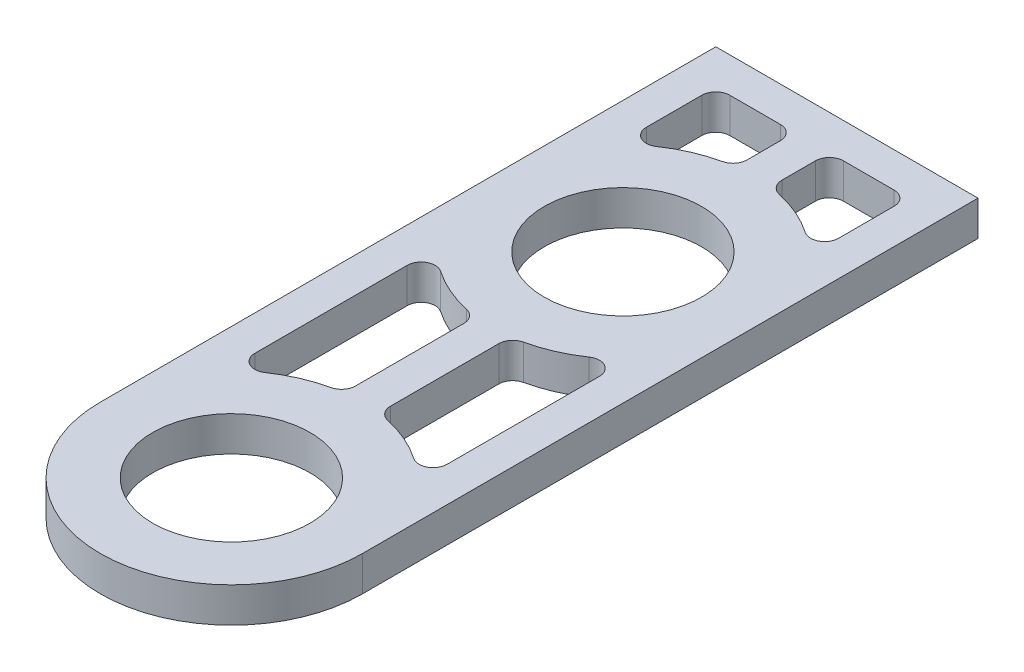
SolidWorks part; units mm, degrees
ref_plane "Front Plane" through (0, 0, 0) normal (0, 0, 1) x (1, 0, 0)
ref_plane "Top Plane" through (0, 0, 0) normal (0, 1, 0) x (1, 0, 0)
ref_plane "Right Plane" through (0, 0, 0) normal (1, 0, 0) x (0, 0, -1)
sketch "Sketch1" plane through (0, 0, 0) normal (0, 1, 0) x (1, 0, 0)
  line L0 (-23.8125, 67.2592) -> (23.8125, 67.2592) construction
  line L1 (-23.8125, -76.2) -> (23.8125, -76.2)
  line L2 (-23.8125, -76.2) -> (-23.8125, 76.2)
  line L3 (-23.8125, 76.2) -> (23.8125, 76.2)
  line L4 (23.8125, -76.2) -> (23.8125, 76.2)
  line L5 (-23.8125, -76.2) -> (23.8125, 76.2) construction
  line L6 (-23.8125, 76.2) -> (23.8125, -76.2) construction
  line L8 (7.3323, -35.6108) -> (3.6662, -29.2608)
  line L9 (3.6662, -29.2608) -> (-3.6662, -29.2608)
  line L10 (-3.6662, -29.2608) -> (-7.3323, -35.6108)
  line L11 (-7.3323, -35.6108) -> (-3.6662, -41.9608)
  line L12 (-3.6662, -41.9608) -> (3.6662, -41.9608)
  line L13 (3.6662, -41.9608) -> (7.3323, -35.6108)
  line L14 (5.4993, 35.5092) -> (2.7496, 40.2717)
  line L15 (2.7496, 40.2717) -> (-2.7496, 40.2717)
  line L16 (-2.7496, 40.2717) -> (-5.4993, 35.5092)
  line L17 (-5.4993, 35.5092) -> (-2.7496, 30.7467)
  line L18 (-2.7496, 30.7467) -> (2.7496, 30.7467)
  line L19 (2.7496, 30.7467) -> (5.4993, 35.5092)
  circle A0 centre (0, 35.5092) radius 14.2875
  circle A1 centre (0, 35.5092) radius 4.7625 construction
  circle A2 centre (0, -35.6108) radius 14.2875
  circle A3 centre (0, -35.6108) radius 6.35 construction
  circle A4 centre (0, 35.5092) radius 31.75
  circle A5 centre (0, -35.6108) radius 53.34
  point P0 (0, 0)
  dimension "D3" = 28.575
  dimension "D4" = 9.525
  dimension "D5" = 28.575
  dimension "D7" = 12.7
  dimension "D9" = 63.5
  dimension "D10" = 106.68
  dimension "D1" = 47.625
  dimension "D2" = 8.9408
  dimension "D6" = 71.12
  dimension "D8" = 152.4
  dimension "D11" = 31.75
extrude "Boss-Extrude1" add sketch "Sketch1" along normal blind 6.35 contours A4 A0 | L4 A5 L2 L1 A2 | A5 L4 L3 L2 A4 | A5 L4 A4 | A5 A4 L2 | A4 A5
sketch "Sketch2" plane through (0, 6.35, 0) normal (0, 1, 0) x (1, 0, 0)
  line L0 (-23.8125, 76.2) -> (23.8125, 76.2)
  line L1 (23.8125, 76.2) -> (23.8125, 38.1)
  line L2 (23.8125, -76.2) -> (23.8125, 76.2) construction
  line L3 (23.8125, 38.1) -> (23.8125, -35.6108)
  line L4 (-23.8125, 76.2) -> (-23.8125, 38.1)
  line L5 (-23.8125, -76.2) -> (-23.8125, 76.2) construction
  line L6 (-23.8125, 38.1) -> (-23.8125, -35.6108)
  line L7 (-17.4625, 19.3198) -> (-17.4625, -19.4214)
  line L8 (17.4625, 19.3198) -> (17.4625, -19.4214)
  line L9 (-17.4625, 51.6986) -> (-17.4625, 69.85)
  line L10 (-17.4625, 69.85) -> (17.4625, 69.85)
  line L11 (0, 35.5092) -> (0, -35.6108) construction
  line L12 (3.175, 11.9093) -> (3.175, -12.0109)
  line L13 (-3.175, 11.9093) -> (-3.175, -12.0109)
  line L14 (17.4625, 69.85) -> (17.4625, 51.6986)
  line L15 (0, 35.5092) -> (0, 69.85) construction
  line L16 (-3.175, 59.1091) -> (-3.175, 69.85)
  line L17 (3.175, 59.1091) -> (3.175, 69.85)
  circle A0 centre (0, 35.5092) radius 23.8125
  circle A1 centre (0, -35.6108) radius 23.8125
  line M2 (-23.8125, 76.2) -> (-23.8125, -76.2)
  line M3 (-23.8125, -76.2) -> (23.8125, -76.2)
  line M4 (23.8125, -76.2) -> (23.8125, 76.2)
  dimension "D1" = 47.625
  dimension "D2" = 47.625
  dimension "D3" = 6.35
  dimension "D4" = 6.35
  dimension "D5" = 6.35
  dimension "D6" = 6.35
  dimension "D7" = 6.35
  dimension "D8" = 6.35
extrude "Cut-Extrude1" cut sketch "Sketch2" against normal through all contours A1 L6 L3 M2 M3 M4 | A0 L16 L10 L9 | A0 L14 L10 L17 | A1 L13 A0 L7 | A1 L8 A0 L12
fillet "Fillet1" radius 2.54 16 edges at (-17.4625, 3.175, 19.4214) (-3.175, 3.175, 12.0109) (17.4625, 3.175, 19.4214) (3.175, 3.175, 12.0109) (-3.175, 3.175, -11.9093) (3.175, 3.175, -11.9093) (-17.4625, 3.175, -19.3198) (17.4625, 3.175, -19.3198) (17.4625, 3.175, -51.6986) (3.175, 3.175, -59.1091) (17.4625, 3.175, -69.85) (3.175, 3.175, -69.85) (-3.175, 3.175, -59.1091) (-17.4625, 3.175, -51.6986) (-3.175, 3.175, -69.85) (-17.4625, 3.175, -69.85)
